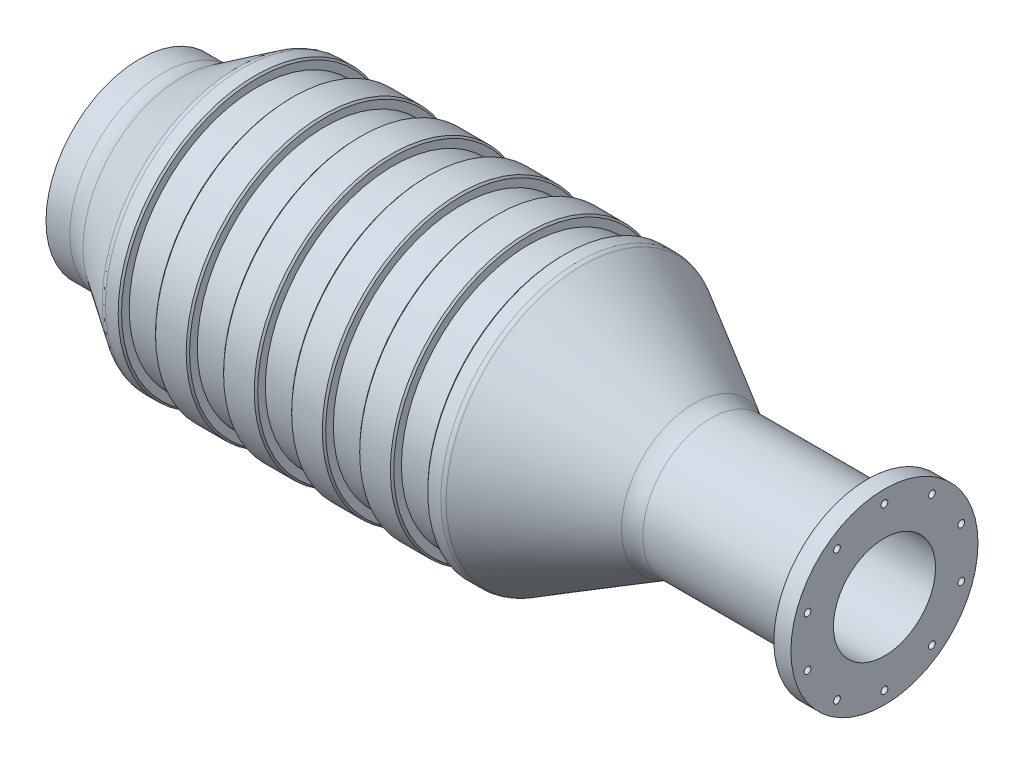
SolidWorks part; units mm, degrees
ref_plane "Front Plane" through (0, 0, 0) normal (0, 0, 1) x (1, 0, 0)
ref_plane "Top Plane" through (0, 0, 0) normal (0, 1, 0) x (1, 0, 0)
ref_plane "Right Plane" through (0, 0, 0) normal (1, 0, 0) x (0, 0, -1)
sketch "Sketch1" plane through (0, 0, 0) normal (0, 0, 1) x (1, 0, 0)
  line L0 (-200, 0) -> (63.7966, 0) construction
  line L6 (227.8815, 55) -> (227.8815, 40)
  line L7 (127.8815, 30) -> (54.1578, 72)
  line L8 (127.8815, 30) -> (54.1578, 72)
  line L9 (127.8815, 30) -> (237.8815, 30)
  line L10 (237.8815, 30) -> (237.8815, 55)
  line L11 (237.8815, 55) -> (227.8815, 55)
  line L12 (227.8815, 40) -> (130.5302, 40)
  line L13 (130.5302, 40) -> (59.1079, 80.6889)
  line L14 (250, 55) -> (217.8815, 55) construction
  line L15 (250, 55) -> (250, 20) construction
  line L16 (240, 45) -> (240, 20) construction
  line L17 (240, 45) -> (227.8815, 45) construction
  line L18 (227.8815, 45) -> (227.8815, 30) construction
  line L19 (217.8815, 55) -> (217.8815, 40) construction
  line L20 (130.5302, 40) -> (217.8815, 40) construction
  line L21 (127.8815, 30) -> (227.8815, 30) construction
  line L22 (127.8815, 30) -> (230.5302, 30) construction
  line L23 (130.5302, 40) -> (230.5302, 40) construction
  line L24 (59.1079, 80.6889) -> (49.1079, 80.6889)
  line L25 (49.1079, 80.6889) -> (49.1079, 75.1889)
  line L26 (49.1079, 75.1889) -> (29.1079, 75.1889)
  line L27 (29.1079, 75.1889) -> (29.1079, 80.6889)
  line L28 (29.1079, 80.6889) -> (9.1079, 80.6889)
  line L29 (9.1079, 80.6889) -> (9.1079, 75.1889)
  line L30 (9.1079, 75.1889) -> (-10.8921, 75.1889)
  line L31 (-10.8921, 75.1889) -> (-10.8921, 80.6889)
  line L32 (-10.8921, 80.6889) -> (-30.8921, 80.6889)
  line L33 (-30.8921, 80.6889) -> (-30.8921, 75.1889)
  line L34 (-30.8921, 75.1889) -> (-50.8921, 75.1889)
  line L35 (-50.8921, 75.1889) -> (-50.8921, 80.6889)
  line L36 (-50.8921, 80.6889) -> (-70.8921, 80.6889)
  line L37 (-70.8921, 80.6889) -> (-70.8921, 75.1889)
  line L38 (-70.8921, 75.1889) -> (-90.8921, 75.1889)
  line L39 (-90.8921, 75.1889) -> (-90.8921, 80.6889)
  line L40 (-90.8921, 80.6889) -> (-110.8921, 80.6889)
  line L41 (-110.8921, 80.6889) -> (-110.8921, 75.1889)
  line L42 (-110.8921, 75.1889) -> (-130.8921, 75.1889)
  line L43 (-130.8921, 75.1889) -> (-130.8921, 80.6889)
  line L44 (-130.8921, 80.6889) -> (-140.8921, 80.6889)
  line L46 (-200, 25) -> (-190, 25)
  line L47 (-200, 25) -> (-200, 55)
  line L48 (-200, 55) -> (-180, 55)
  line L49 (-180, 55) -> (-140.8921, 80.6889)
  line L50 (-190, 25) -> (-190, 45)
  line L51 (-181.1866, 45) -> (-190, 45)
  line L53 (-169.9695, 48.4417) -> (-140.9985, 68.0675)
  line L54 (54.1578, 72) -> (-129.8348, 71.5092)
  arc A0 (-181.1866, 45) -> (-169.9695, 48.4417) centre (-181.1866, 65) ccw
  arc A1 (-129.8348, 71.5092) -> (-140.9985, 68.0675) centre (-129.7814, 51.5093) ccw
  dimension "D2" = 20
  dimension "D1" = 10
  dimension "D3" = 10
revolve "Revolve1" add sketch "Sketch1" angle 360 about L0
fillet "Fillet1" radius 20 2 edges at (-180, 0, 55) (130.5302, 0, 40)
chamfer "Chamfer1" distance 1 angle 45 10 edges at (49.1079, 0, 80.6889) (29.1079, 0, 80.6889) (9.1079, 0, 80.6889) (-10.8921, 0, 80.6889) (-30.8921, 0, 80.6889) (-50.8921, 0, 80.6889) (-70.8921, 0, 80.6889) (-90.8921, 0, 80.6889) (-110.8921, 0, 80.6889) (-130.8921, 0, 80.6889)
fillet "Fillet2" radius 5 3 edges at (227.8815, 0, 40) (59.1079, 0, 80.6889) (-140.8921, 0, 80.6889)
sketch "Sketch3" plane through (-200, 0, 0) normal (-1, 0, 0) x (0, 0, 1)
  circle A0 centre (0, 45) radius 2
  dimension "D1" = 45
extrude "Cut-Extrude2" cut sketch "Sketch3" against normal blind 10
sketch "Sketch4" plane through (237.8815, 0, 0) normal (1, 0, 0) x (0, 0, -1)
  circle A0 centre (0, 47.5) radius 2
  dimension "D1" = 47.5
extrude "Cut-Extrude3" cut sketch "Sketch4" against normal blind 10
pattern_circular "CirPattern2" count 10 over 360 about axis through (0, 0, 0) along (1, 0, 0) of "Cut-Extrude2", "Cut-Extrude3"
